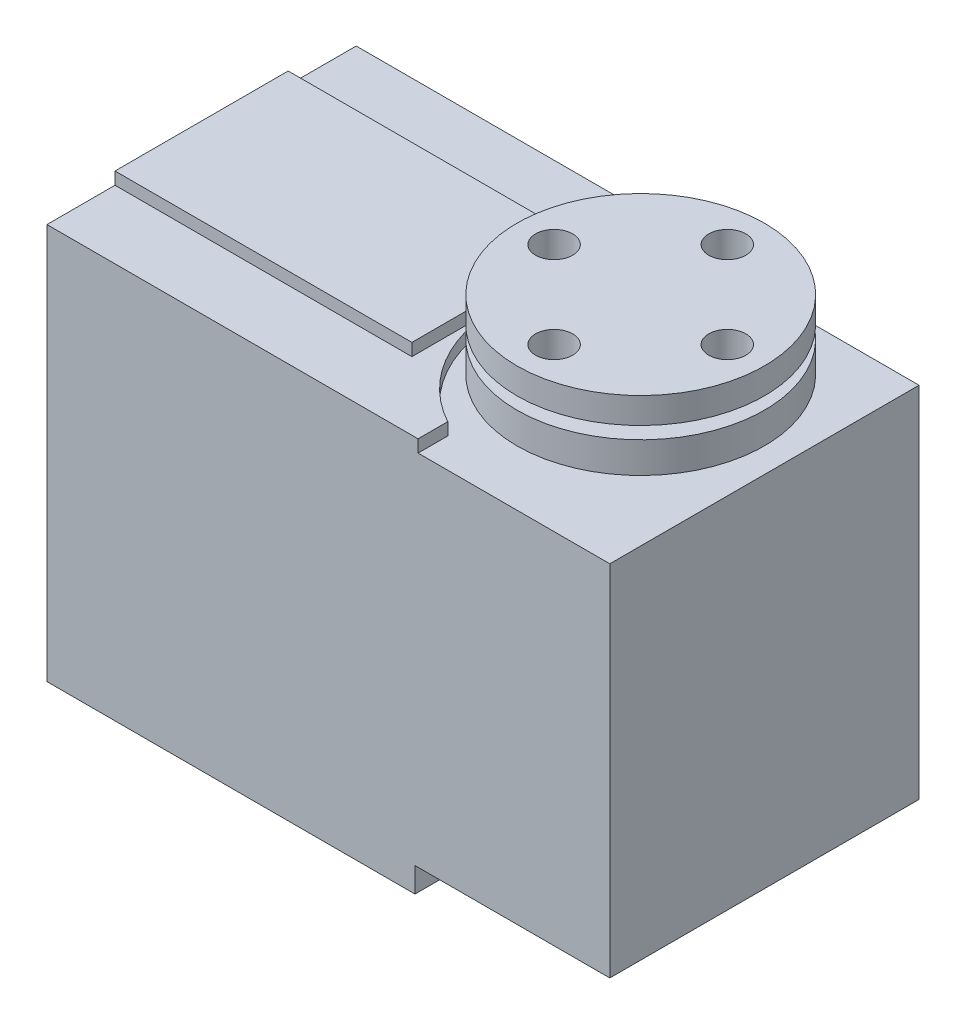
SolidWorks part; units mm, degrees
ref_plane "Front Plane" through (0, 0, 0) normal (0, 0, 1) x (1, 0, 0)
ref_plane "Top Plane" through (0, 0, 0) normal (0, 1, 0) x (1, 0, 0)
ref_plane "Right Plane" through (0, 0, 0) normal (1, 0, 0) x (0, 0, -1)
sketch "Main Body Sketch" plane through (0, 0, 0) normal (0, 1, 0) x (1, 0, 0)
  line L1 (-22.75, 12.5) -> (22.75, 12.5)
  line L2 (-22.75, 12.5) -> (-22.75, -12.5)
  line L3 (-22.75, -12.5) -> (22.75, -12.5)
  line L4 (22.75, 12.5) -> (22.75, -12.5)
  point P4 (0, 12.5)
  point P6 (-22.75, 0)
  dimension "D1" = 45.5
  dimension "D2" = 25
extrude "Main Body Extrusion" add sketch "Main Body Sketch" along normal blind 29
sketch "Sketch2" plane through (0, 29, 0) normal (0, 1, 0) x (1, 0, 0)
  line L0 (-22.75, 12.5) -> (-22.75, -12.5) construction
  line L1 (-22.75, 12.5) -> (7.25, 12.5)
  line L2 (-22.75, 12.5) -> (-22.75, -12.5)
  line L3 (-22.75, -12.5) -> (7.25, -12.5)
  line L4 (7.25, 12.5) -> (7.25, 10.0995)
  line L5 (7.25, -10.0995) -> (7.25, -12.5)
  line L6 (22.75, 12.5) -> (-22.75, 12.5) construction
  line L7 (22.75, -12.5) -> (22.75, 12.5) construction
  arc A1 (7.25, 10.0995) -> (7.25, -10.0995) centre (12.75, 0) ccw
  point P14 (22.75, 0)
  dimension "D1" = 11.5
  dimension "D2" = 30
  dimension "D3" = 10
extrude "Boss-Extrude3" add sketch "Sketch2" along normal blind 1
sketch "Sketch8" plane through (0, 30, 0) normal (0, 1, 0) x (1, 0, 0)
  line L0 (-22.75, 12.5) -> (-22.75, -12.5) construction
  line L1 (-22.75, 7) -> (1.25, 7)
  line L2 (-22.75, 7) -> (-22.75, -7)
  line L3 (-22.75, -7) -> (1.25, -7)
  line L4 (1.25, 7) -> (1.25, -7)
  arc A0 (7.25, 10.0995) -> (7.25, -10.0995) centre (12.75, 0) ccw construction
  point P6 (-22.75, 0)
  point P7 (1.25, 0)
  dimension "D1" = 14
extrude "Boss-Extrude8" add sketch "Sketch8" along normal blind 1
sketch "Sketch3" plane through (0, 29, 0) normal (0, 1, 0) x (1, 0, 0)
  line L0 (22.75, -12.5) -> (22.75, 12.5) construction
  circle A0 centre (12.75, 0) radius 2.25
  point P5 (22.75, 0)
  dimension "D2" = 4.5
  dimension "D1" = 10
extrude "Boss-Extrude4" add sketch "Sketch3" along normal blind 2
sketch "Sketch4" plane through (0, 0, 0) normal (0, -1, 0) x (1, 0, 0)
  line L0 (22.75, 12.5) -> (22.75, -12.5) construction
  line L1 (0, 12.5) -> (0, -12.5) construction
  line L2 (-22.75, 12.5) -> (22.75, 12.5) construction
  line L3 (22.75, -12.5) -> (-22.75, -12.5) construction
  circle A0 centre (12.5, 0) radius 3
  circle A1 centre (12.5, 0) radius 1.25
  point P4 (22.75, 0)
  dimension "D1" = 6
  dimension "D3" = 2.5
  dimension "D2" = 12.5
sketch "Sketch5" plane through (0, 0, 0) normal (0, -1, 0) x (1, 0, 0)
  line L0 (-22.75, -12.5) -> (-22.75, 12.5) construction
  line L1 (-22.75, 12.5) -> (-4, 12.5)
  line L2 (-22.75, 12.5) -> (-22.75, -12.5)
  line L3 (-22.75, -12.5) -> (-4, -12.5)
  line L4 (-4, 12.5) -> (-4, -12.5)
  line L5 (-22.75, 12.5) -> (22.75, 12.5) construction
  line L6 (1, 10) -> (1, 6.5)
  line L7 (-4, 12.5) -> (7, 12.5)
  line L8 (-4, 12.5) -> (-4, 10)
  line L9 (-4, 10) -> (1, 10)
  line L10 (7, 12.5) -> (7, 10)
  line L11 (1, 6.5) -> (3.5, 6.5)
  line L12 (3.5, 6.5) -> (7, 10)
  line L13 (-20.9143, 0) -> (8.4235, 0) construction
  line L14 (3.5, -6.5) -> (7, -10)
  line L15 (1, -6.5) -> (3.5, -6.5)
  line L16 (7, -12.5) -> (7, -10)
  line L17 (-4, -10) -> (1, -10)
  line L18 (-4, -12.5) -> (7, -12.5)
  line L19 (1, -10) -> (1, -6.5)
  line L21 (22.75, 12.5) -> (22.75, -12.5) construction
  point P6 (-22.75, 0)
  point P7 (-22.75, 0)
  line M7 (-22.75, -12.5) -> (22.75, -12.5)
  line M9 (22.75, 12.5) -> (-22.75, 12.5)
  dimension "D1" = 18.75
  dimension "D3" = 11
  dimension "D4" = 2.5
  dimension "D5" = 3.5
  dimension "D6" = 2.5
  dimension "D7" = 21.75
sketch "Sketch6" plane through (0, 31, 0) normal (0, 1, 0) x (1, 0, 0)
  circle A0 centre (12.75, 0) radius 10
  circle A1 centre (12.75, 0) radius 2.25 construction
  dimension "D1" = 20
extrude "Boss-Extrude7" add sketch "Sketch6" along normal blind 2.5
sketch "Sketch7" plane through (0, 33.5, 0) normal (0, 1, 0) x (1, 0, 0)
  line L0 (12.75, 0) -> (12.75, 7) construction
  line L1 (5.75, 0) -> (12.75, 0) construction
  circle A0 centre (12.75, 0) radius 10 construction
  circle A1 centre (12.75, 7) radius 1.5
  circle A2 centre (12.75, -7) radius 1.5
  circle A3 centre (5.75, 0) radius 1.5
  circle A4 centre (19.75, 0) radius 1.5
  dimension "D2" = 3
  dimension "D1" = 7
extrude "Cut-Extrude1" cut sketch "Sketch7" against normal blind 2
sketch "Sketch10" plane through (0, 33.5, 0) normal (0, 1, 0) x (1, 0, 0)
  circle A0 centre (12.75, 0) radius 2.25
  circle A1 centre (12.75, 0) radius 10 construction
  dimension "D1" = 4.5
extrude "Boss-Extrude12" add sketch "Sketch10" along normal blind 1
sketch "Sketch11" plane through (0, 34.5, 0) normal (0, 1, 0) x (1, 0, 0)
  circle A0 centre (12.75, 0) radius 10
  circle A1 centre (12.75, 0) radius 2.25 construction
  dimension "D1" = 20
extrude "Boss-Extrude13" add sketch "Sketch11" along normal blind 2.1
sketch "Sketch13" plane through (0, 36.6, 0) normal (0, 1, 0) x (1, 0, 0)
  line L0 (12.75, 0) -> (5.75, 0) construction
  line L1 (12.75, 7) -> (12.75, 0) construction
  circle A0 centre (12.75, 0) radius 10 construction
  circle A1 centre (12.75, 7) radius 1.5
  circle A2 centre (5.75, 0) radius 1.5
  circle A3 centre (12.75, -7) radius 1.5
  circle A4 centre (19.75, 0) radius 1.5
  dimension "D1" = 3
  dimension "D2" = 7
extrude "Cut-Extrude3" cut sketch "Sketch13" against normal blind 2.1
extrude "Boss-Extrude9" add sketch "Sketch5" along normal blind 2 contours L11 L12 L10 L4 L9 L6 M9 | L13 L2 L4 M7 | L19 L17 L4 L16 L14 L15 M7
sketch "Sketch9" plane through (0, 0, 0) normal (0, -1, 0) x (1, 0, 0)
  line L1 (1, 10) -> (-4, 10)
  line L2 (1, 10) -> (1, -10)
  line L3 (1, -10) -> (-4, -10)
  line L4 (-4, 10) -> (-4, -10)
extrude "Cut-Extrude2" cut sketch "Sketch9" against normal blind 5
extrude "Boss-Extrude10" add sketch "Sketch4" along normal blind 4.1
sketch "Sketch14" plane through (0, -2, 0) normal (0, -1, 0) x (1, 0, 0)
  line L0 (-4, 10) -> (-4, -10) construction
  line L1 (-4, 8.9073) -> (-17.5, 8.9073)
  line L2 (-4, 8.9073) -> (-4, -8.9488)
  line L3 (-4, -8.9488) -> (-17.5, -8.9488)
  line L4 (-17.5, 8.9073) -> (-17.5, -8.9488)
  dimension "D1" = 13.5
extrude "Boss-Extrude14" add sketch "Sketch14" along normal blind 2
